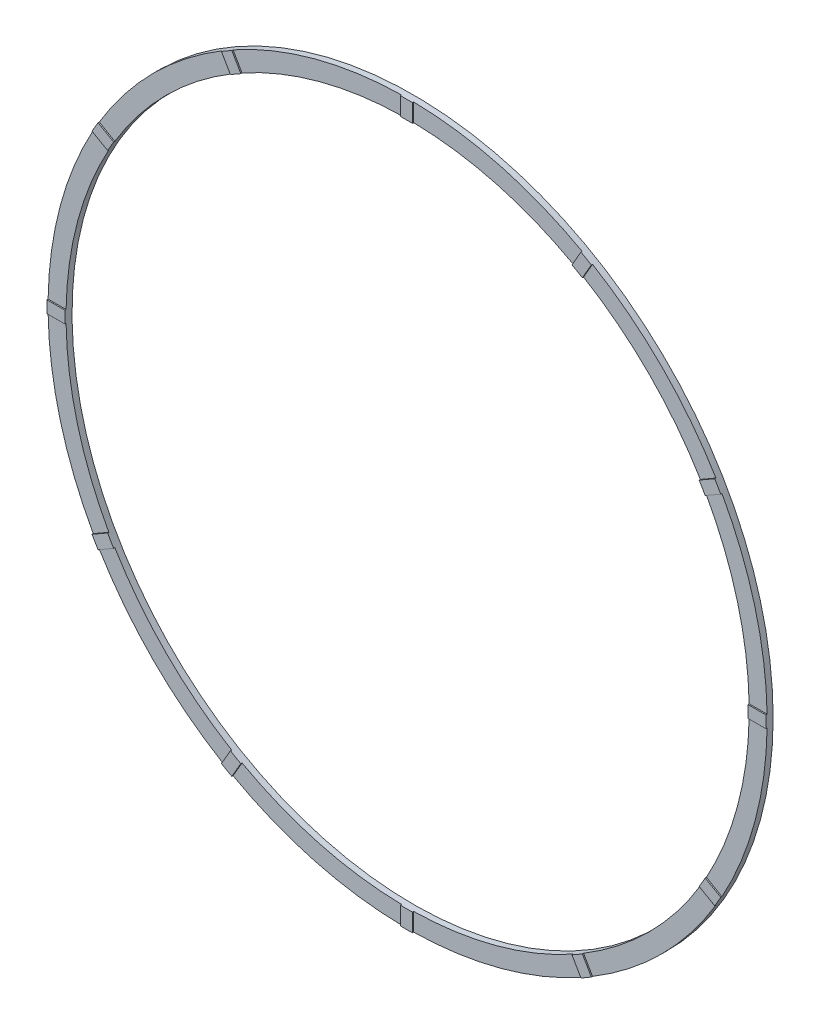
SolidWorks part; units mm, degrees
ref_plane "Front Plane" through (0, 0, 0) normal (0, 0, 1) x (1, 0, 0)
ref_plane "Top Plane" through (0, 0, 0) normal (0, 1, 0) x (1, 0, 0)
ref_plane "Right Plane" through (0, 0, 0) normal (1, 0, 0) x (0, 0, -1)
sketch "Sketch1" plane through (0, 0, 0) normal (0, 0, 1) x (1, 0, 0)
  line L0 (0, 0) -> (0, 13.7119) construction
  circle A0 centre (0, 0) radius 28.5
  circle A1 centre (0, 0) radius 30
  dimension "D1" = 57
  dimension "D2" = 60
extrude "Boss-Extrude2" add sketch "Sketch1" along normal blind 0.5 contours A1 A0
sketch "Sketch2" plane through (0, 0, 0.5) normal (0, 0, 1) x (1, 0, 0)
  line L0 (0, 0) -> (0, 37.2158) construction
  line L1 (14.5649, 26.2272) -> (13.8148, 24.9279)
  line L2 (15.4309, 25.7272) -> (14.6808, 24.4279)
  line L3 (-0.5, 29.9958) -> (-0.5, 28.4956)
  line L4 (25.7272, 15.4309) -> (24.4279, 14.6808)
  line L5 (0.5, 29.9958) -> (0.5, 28.4956)
  line L6 (26.2272, 14.5649) -> (24.9279, 13.8148)
  line L7 (29.9958, 0.5) -> (28.4956, 0.5)
  line L8 (29.9958, -0.5) -> (28.4956, -0.5)
  line L9 (26.2272, -14.5649) -> (24.9279, -13.8148)
  line L10 (25.7272, -15.4309) -> (24.4279, -14.6808)
  line L11 (15.4309, -25.7272) -> (14.6808, -24.4279)
  line L12 (14.5649, -26.2272) -> (13.8148, -24.9279)
  line L13 (0.5, -29.9958) -> (0.5, -28.4956)
  line L14 (-0.5, -29.9958) -> (-0.5, -28.4956)
  line L15 (-14.5649, -26.2272) -> (-13.8148, -24.9279)
  line L16 (-15.4309, -25.7272) -> (-14.6808, -24.4279)
  line L17 (-25.7272, -15.4309) -> (-24.4279, -14.6808)
  line L18 (-26.2272, -14.5649) -> (-24.9279, -13.8148)
  line L19 (-29.9958, -0.5) -> (-28.4956, -0.5)
  line L20 (-29.9958, 0.5) -> (-28.4956, 0.5)
  line L21 (-26.2272, 14.5649) -> (-24.9279, 13.8148)
  line L22 (-25.7272, 15.4309) -> (-24.4279, 14.6808)
  line L23 (-15.4309, 25.7272) -> (-14.6808, 24.4279)
  line L24 (-14.5649, 26.2272) -> (-13.8148, 24.9279)
  arc A0 (-13.8148, 24.9279) -> (-14.6808, 24.4279) centre (0, 0) ccw
  arc A1 (-14.5649, 26.2272) -> (-15.4309, 25.7272) centre (0, 0) ccw
  arc A2 (0.5, 29.9958) -> (-0.5, 29.9958) centre (0, 0) ccw
  arc A3 (0.5, 28.4956) -> (-0.5, 28.4956) centre (0, 0) ccw
  arc A4 (14.6808, 24.4279) -> (13.8148, 24.9279) centre (0, 0) ccw
  arc A5 (15.4309, 25.7272) -> (14.5649, 26.2272) centre (0, 0) ccw
  arc A6 (24.9279, 13.8148) -> (24.4279, 14.6808) centre (0, 0) ccw
  arc A7 (26.2272, 14.5649) -> (25.7272, 15.4309) centre (0, 0) ccw
  arc A8 (-24.4279, 14.6808) -> (-24.9279, 13.8148) centre (0, 0) ccw
  arc A9 (-25.7272, 15.4309) -> (-26.2272, 14.5649) centre (0, 0) ccw
  arc A10 (-29.9958, 0.5) -> (-29.9958, -0.5) centre (0, 0) ccw
  arc A11 (-28.4956, 0.5) -> (-28.4956, -0.5) centre (0, 0) ccw
  arc A12 (-26.2272, -14.5649) -> (-25.7272, -15.4309) centre (0, 0) ccw
  arc A13 (-24.9279, -13.8148) -> (-24.4279, -14.6808) centre (0, 0) ccw
  arc A14 (-14.6808, -24.4279) -> (-13.8148, -24.9279) centre (0, 0) ccw
  arc A15 (-15.4309, -25.7272) -> (-14.5649, -26.2272) centre (0, 0) ccw
  arc A16 (-0.5, -29.9958) -> (0.5, -29.9958) centre (0, 0) ccw
  arc A17 (-0.5, -28.4956) -> (0.5, -28.4956) centre (0, 0) ccw
  arc A18 (13.8148, -24.9279) -> (14.6808, -24.4279) centre (0, 0) ccw
  arc A19 (14.5649, -26.2272) -> (15.4309, -25.7272) centre (0, 0) ccw
  arc A20 (25.7272, -15.4309) -> (26.2272, -14.5649) centre (0, 0) ccw
  arc A21 (24.4279, -14.6808) -> (24.9279, -13.8148) centre (0, 0) ccw
  arc A22 (29.9958, -0.5) -> (29.9958, 0.5) centre (0, 0) ccw
  arc A23 (28.4956, -0.5) -> (28.4956, 0.5) centre (0, 0) ccw
  point P55 (0, 0)
  dimension "D1" = 60
  dimension "D2" = 57
  dimension "D3" = 1
  dimension "D4" = 0.5
  dimension "D5" = 12
extrude "Boss-Extrude4" add sketch "Sketch2" along normal blind 0.1
